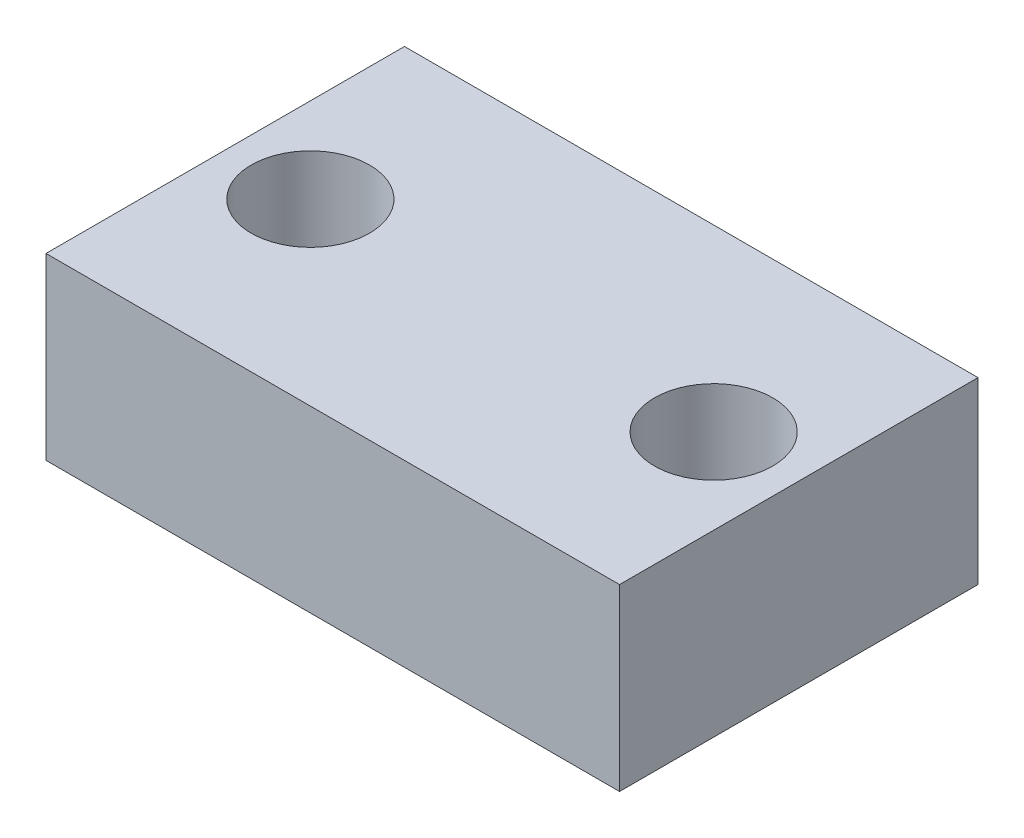
SolidWorks part; units mm, degrees
ref_plane "Alzado" through (0, 0, 0) normal (0, 0, 1) x (1, 0, 0)
ref_plane "Planta" through (0, 0, 0) normal (0, 1, 0) x (1, 0, 0)
ref_plane "Vista lateral" through (0, 0, 0) normal (1, 0, 0) x (0, 0, -1)
sketch "Croquis1" plane through (0, 0, 0) normal (0, 1, 0) x (1, 0, 0)
  line L1 (-8, -5) -> (8, -5)
  line L2 (-8, -5) -> (-8, 5)
  line L3 (-8, 5) -> (8, 5)
  line L4 (8, -5) -> (8, 5)
  point P0 (0, 0)
  dimension "D1" = 16
  dimension "D2" = 10
extrude "Saliente-Extruir1" add sketch "Croquis1" along normal blind 5 contours L3 L4 L1 L2
sketch "Croquis2" plane through (0, 0, 0) normal (0, -1, 0) x (1, 0, 0)
  line L2 (-8, 5) -> (8, 5) construction
  line L3 (8, 5) -> (8, -5) construction
  circle A0 centre (-5.625, 0) radius 1.65
  circle A1 centre (5.625, 0) radius 1.65
  dimension "D1" = 3.3
  dimension "D2" = 3.3
  dimension "D3" = 5
  dimension "D4" = 2.375
  dimension "D5" = 11.25
  dimension "D6" = 5
extrude "Cortar-Extruir1" cut sketch "Croquis2" against normal up to next
